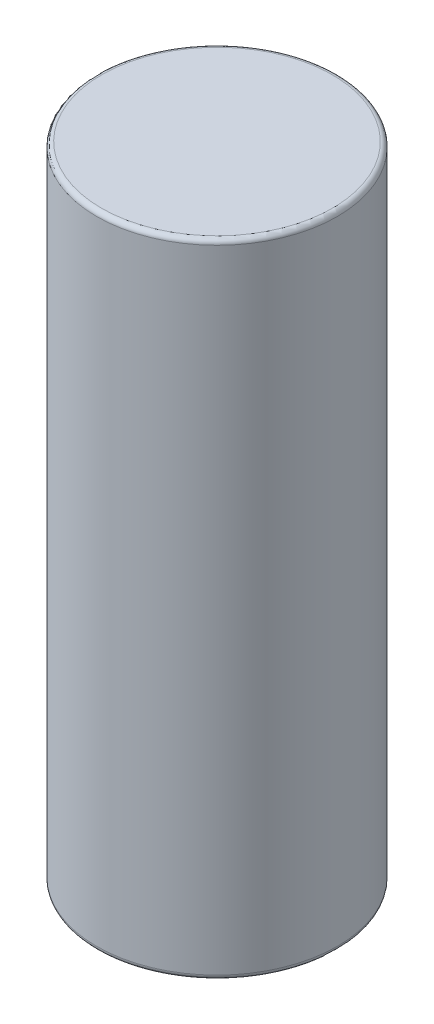
SolidWorks part; units mm, degrees
ref_plane "Front Plane" through (0, 0, 0) normal (0, 0, 1) x (1, 0, 0)
ref_plane "Top Plane" through (0, 0, 0) normal (0, 1, 0) x (1, 0, 0)
ref_plane "Right Plane" through (0, 0, 0) normal (1, 0, 0) x (0, 0, -1)
sketch "Sketch1" plane through (0, 0, 0) normal (0, 0, 1) x (1, 0, 0)
  line L0 (0, 0) -> (0, 80999.8346) construction
  line L1 (0, 200) -> (0, -200)
  line L2 (0, -200) -> (75, -200)
  line L4 (0, 200) -> (75, 200)
  line L5 (75, -200) -> (75, 200)
  line L6 (0, 0) -> (75, 200) construction
  line L7 (0, 0) -> (75, -200) construction
  point P3 (0, 0)
  dimension "D1" = 150
  dimension "D2" = 400
revolve "Revolve1" add sketch "Sketch1" angle 360 about L0
fillet "Fillet1" radius 3 2 edges at (0, -200, -75) (0, 200, -75)
equation "\"CanSat_Len\"= 400mm"
equation "\"CanSat_Dia\"= 150mm"
equation "\"BodyTube_ID\"= 114mm"
equation "\"BodyTube_OD\"= 120mm"
equation "\"PayLoadBay_ID\"= 164mm"
equation "\"PayLoadBay_OD\"= 170mm"
equation "\"ParachuteBay_Pitch\"= 300mm"
equation "\"ElectronicsTray_PitchDist\"= 50mm"
equation "\"ElectronicsTray_Height\"= 140mm"
equation "\"MotorDia\"= 98mm"
equation "\"MotorLen\"= 289mm"
equation "\"NosePlateDia\"= 156.6mm"
equation "\"D2@Sketch1\"=\"CanSat_Len\""
